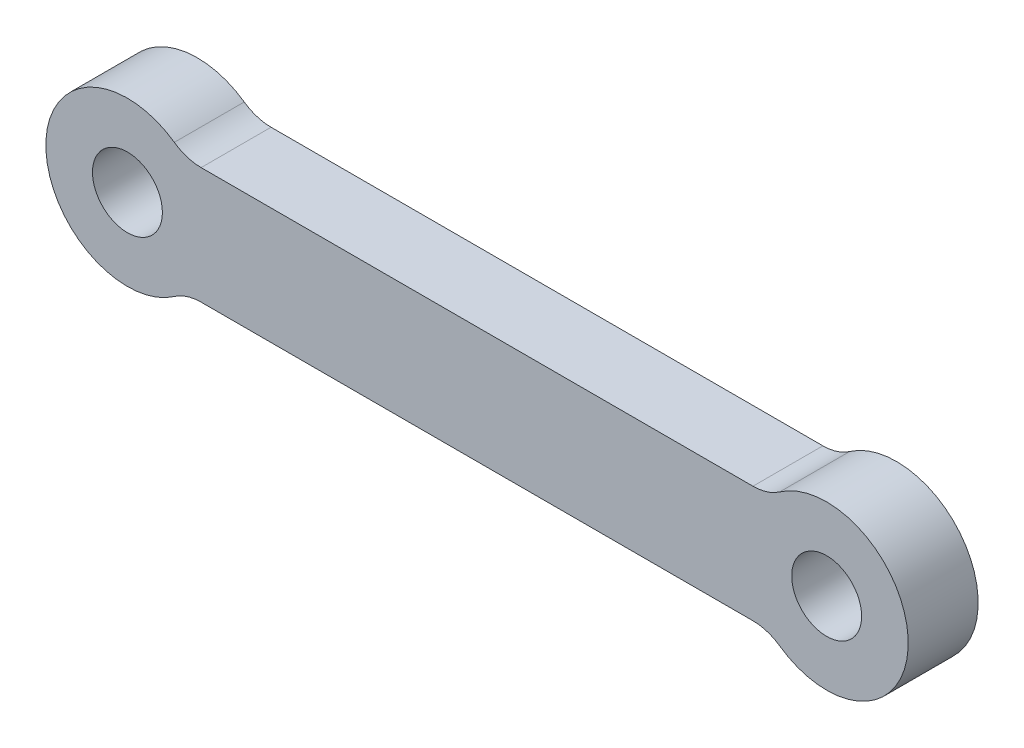
SolidWorks part; units mm, degrees
ref_plane "前视基准面" through (0, 0, 0) normal (0, 0, 1) x (1, 0, 0)
ref_plane "上视基准面" through (0, 0, 0) normal (0, 1, 0) x (1, 0, 0)
ref_plane "右视基准面" through (0, 0, 0) normal (1, 0, 0) x (0, 0, -1)
sketch "草图1" plane through (0, 0, 0) normal (0, 0, 1) x (1, 0, 0)
  line L0 (-11.7237, 0) -> (31.9737, 0) construction
  line L1 (15, 3.902) -> (15, -4.7147) construction
  line L2 (3.1623, 2.5) -> (26.8377, 2.5)
  line L3 (3.1623, -2.5) -> (26.8377, -2.5)
  circle A0 centre (0, 0) radius 1.5
  circle A1 centre (30, 0) radius 1.5
  arc A2 (2.0124, 2.8636) -> (2.0124, -2.8636) centre (0, 0) ccw
  arc A3 (27.9876, 2.8636) -> (27.9876, -2.8636) centre (30, 0) cw
  arc A4 (26.8377, -2.5) -> (27.9876, -2.8636) centre (26.8377, -4.5) cw
  arc A5 (3.1623, -2.5) -> (2.0124, -2.8636) centre (3.1623, -4.5) ccw
  arc A6 (27.9876, 2.8636) -> (26.8377, 2.5) centre (26.8377, 4.5) cw
  arc A7 (3.1623, 2.5) -> (2.0124, 2.8636) centre (3.1623, 4.5) cw
  point P17 (27.5505, -2.5)
  point P20 (2.4495, -2.5)
  point P23 (27.5505, 2.5)
  point P26 (2.4495, 2.5)
  dimension "D1" = 3
  dimension "D2" = 30
  dimension "D3" = 7
  dimension "D4" = 2
  dimension "D5" = 5
extrude "凸台-拉伸1" add sketch "草图1" along normal blind 3
